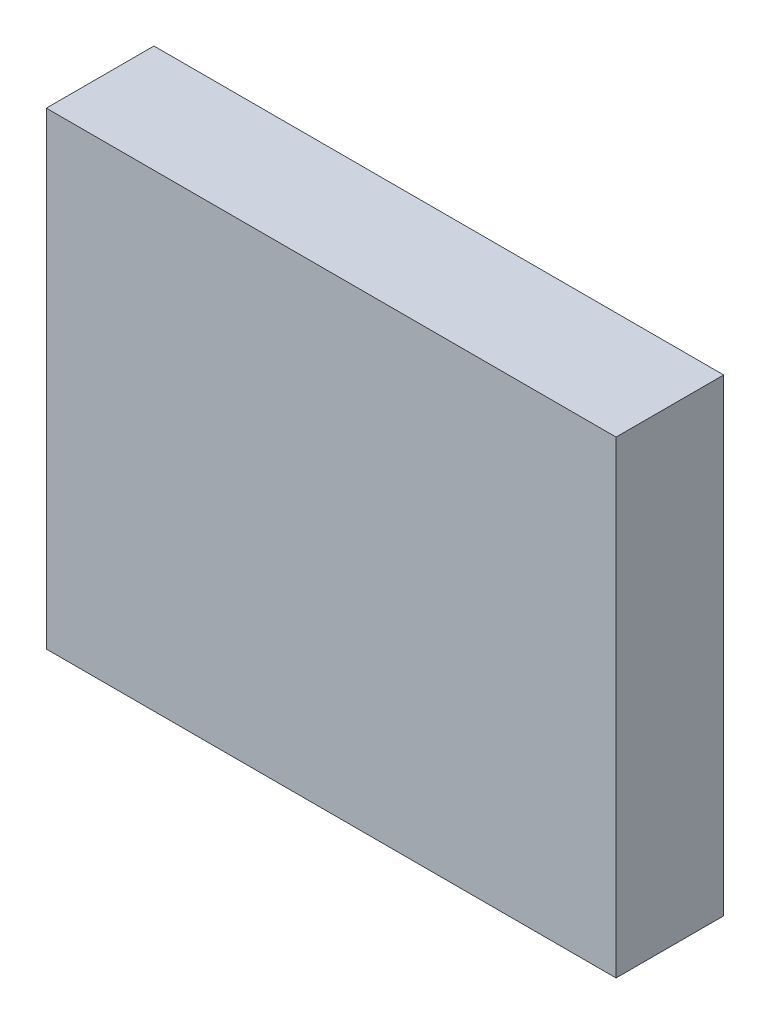
SolidWorks part; units mm, degrees
ref_plane "前视基准面" through (0, 0, 0) normal (0, 0, 1) x (1, 0, 0)
ref_plane "上视基准面" through (0, 0, 0) normal (0, 1, 0) x (1, 0, 0)
ref_plane "右视基准面" through (0, 0, 0) normal (1, 0, 0) x (0, 0, -1)
sketch "草图1" plane through (0, 0, 0) normal (0, 0, 1) x (1, 0, 0)
  line L1 (0, 0) -> (45, 0)
  line L2 (0, 0) -> (0, 37)
  line L3 (0, 37) -> (45, 37)
  line L4 (45, 0) -> (45, 37)
  dimension "D1" = 45
  dimension "D2" = 37
extrude "凸台-拉伸1" add sketch "草图1" along normal blind 8.5 contours L3 L4 L1 L2
